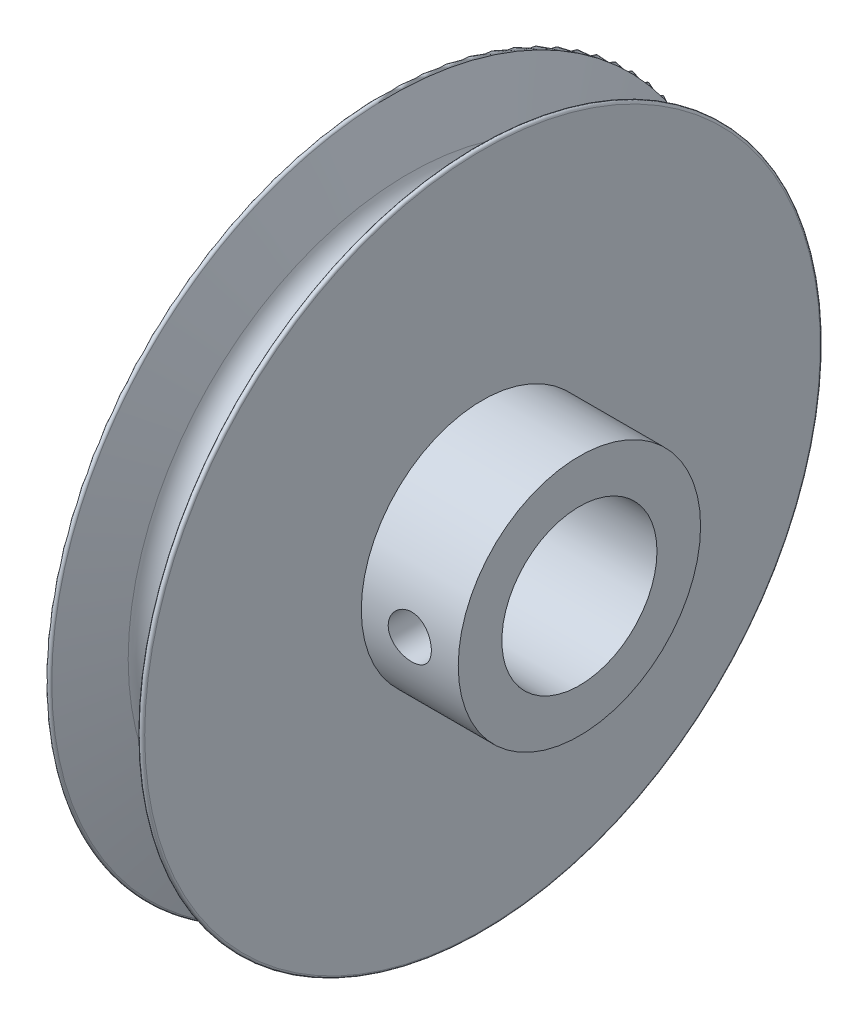
SolidWorks part; units mm, degrees
material "6061-T6 (SS)"
ref_plane "Front Plane" through (0, 0, 0) normal (0, 0, 1) x (1, 0, 0)
ref_plane "Top Plane" through (0, 0, 0) normal (0, 1, 0) x (1, 0, 0)
ref_plane "Right Plane" through (0, 0, 0) normal (1, 0, 0) x (0, 0, -1)
sketch "Sketch1" plane through (0, 0, 0) normal (0, 0, 1) x (1, 0, 0)
  line L0 (-602.9216, 0) -> (29543.159, 0) construction
  line L1 (-601.7144, 17.78) -> (29544.3662, 17.78) construction
  line L2 (0, 17.78) -> (0, -0.2516) construction
  line L3 (-1.905, 0) -> (-1.905, 16.51) construction
  line L7 (1.905, 0) -> (-1.905, 0)
  line L9 (1.905, 0) -> (1.905, 16.51) construction
  line L10 (-1.905, 16.51) -> (-1.3324, 14.6931)
  line L11 (1.905, 16.51) -> (1.3324, 14.6931)
  line L12 (1.905, 16.51) -> (2.54, 18.5249)
  line L13 (2.54, 18.5249) -> (2.54, 0)
  line L14 (-2.54, 0) -> (-2.54, 18.5249)
  line L15 (-2.54, 18.5249) -> (-1.905, 16.51)
  line L16 (-2.54, 0) -> (-1.905, 0)
  line L17 (1.905, 0) -> (2.54, 0)
  circle A1 centre (0, 15.113) radius 1.397 construction
  arc A3 (-1.3324, 14.6931) -> (1.3324, 14.6931) centre (0, 15.113) ccw
  point P14 (0, 0)
  point P23 (0, 16.51)
  dimension "D3" = 2.794
  dimension "D4" = 3.81
  dimension "D1" = 17.78
  dimension "D2" = 16.51
  dimension "D5" = 15.113
  dimension "D6" = 0.635
revolve "Revolve1" add sketch "Sketch1" angle 360 about L0
fillet "Fillet1" radius 0.127 2 edges at (-2.54, 0, 18.5249) (2.54, 0, 18.5249)
sketch "Sketch2" plane through (2.54, 0, 0) normal (1, 0, 0) x (0, 0, -1)
  circle A0 centre (0, 0) radius 6.35
  dimension "D1" = 12.7
extrude "Boss-Extrude1" add sketch "Sketch2" along normal blind 5.08
sketch "Sketch3" plane through (7.62, 0, 0) normal (1, 0, 0) x (0, 0, -1)
  circle A0 centre (0, 0) radius 4.064
  dimension "D1" = 8.128
extrude "Cut-Extrude1" cut sketch "Sketch3" against normal through all
ref_plane "Plane1" through (0, 0, 6.35) normal (0, 0, 1) x (1, 0, 0)
hole_wizard "#4-40 Tapped Hole1" positions "Sketch4" profile "Sketch5" tap size "#4-40" standard "ANSI Inch"
sketch "Sketch4" plane through (0, 0, 6.35) normal (0, 0, 1) x (1, 0, 0)
  line L0 (7.62, -6.35) -> (7.62, 6.35) construction
  line L1 (5.588, 0) -> (-5.588, 0) construction
  point P0 (5.08, 0)
  dimension "D1" = 2.54
sketch "Sketch5" plane through (5.08, 0, 6.35) normal (1, 0, 0) x (0, -1, 0)
  line L0 (0, 0) -> (0, 2.286)
  line L1 (0, 2.286) -> (1.1303, 2.286)
  line L2 (1.1303, 2.286) -> (1.1303, 0)
  line L5 (1.1303, 0) -> (0, 0)
  line L11 (0, -6.35) -> (0, 107.95) construction
  dimension "Thru Tap Drill Dia." = 2.2606
  dimension "Thru Tap Drill Depth" = 2.286
cosmetic thread "Hole Thread1" parameters "D2"=2.8448
